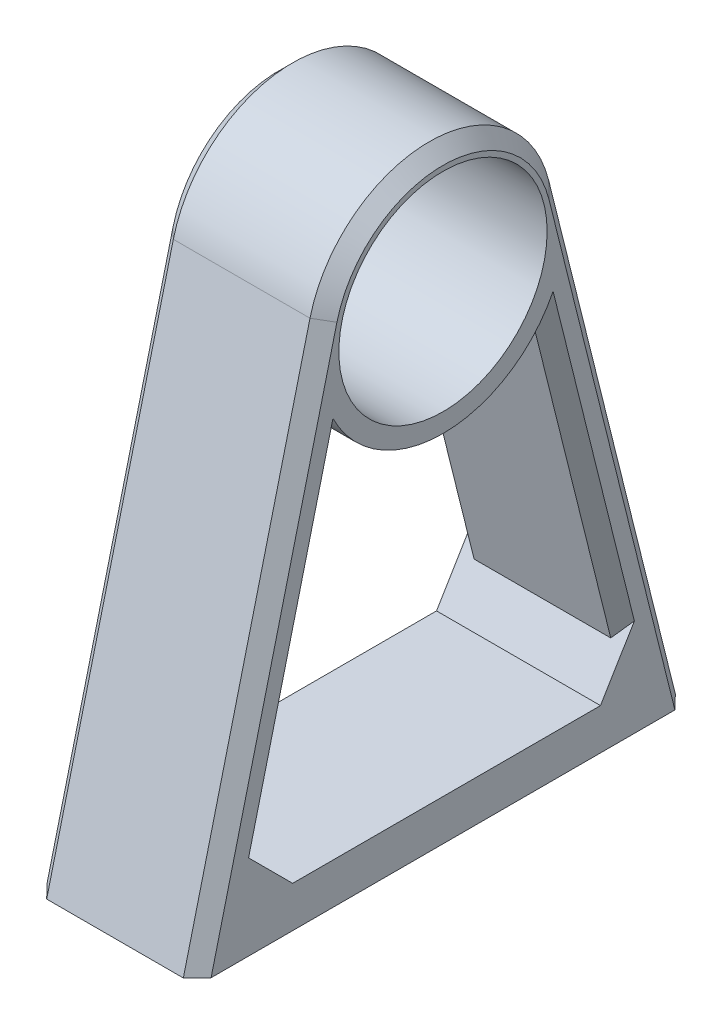
SolidWorks part; units mm, degrees
material "1060-H16"
ref_plane "Płaszczyzna przednia" through (0, 0, 0) normal (0, 0, 1) x (1, 0, 0)
ref_plane "Płaszczyzna górna" through (0, 0, 0) normal (0, 1, 0) x (1, 0, 0)
ref_plane "Płaszczyzna prawa" through (0, 0, 0) normal (1, 0, 0) x (0, 0, -1)
sketch "Szkic1" plane through (0, 0, 0) normal (1, 0, 0) x (0, 0, -1)
  line L0 (0, -45) -> (0, -175)
  line L1 (0, -175) -> (-90, -175)
  line L2 (0, -175) -> (90, -175)
  line L3 (-90, -175) -> (-43.6639, 10.8843)
  line L4 (90, -175) -> (43.6639, 10.8843)
  line L5 (0, -160) -> (70, -160)
  line L6 (0, -160) -> (-70, -160)
  line L7 (-70, -160) -> (-36.6314, -26.137)
  line L8 (70, -160) -> (36.6314, -26.137)
  circle A0 centre (0, 0) radius 38.1
  arc A1 (-36.6314, -26.137) -> (36.6314, -26.137) centre (0, 0) ccw
  arc A2 (43.6639, 10.8843) -> (-43.6639, 10.8843) centre (0, 0) ccw
  dimension "D1" = 76.2
  dimension "D2" = 90
  dimension "D3" = 130
  dimension "D4" = 90
  dimension "D5" = 90
  dimension "D6" = 70
  dimension "D7" = 70
  dimension "D8" = 15
extrude "Dodanie-wyciągnięcie1" add sketch "Szkic1" along normal mid plane 60
chamfer "Sfazowanie1" distance 15 angle 45 2 edges at (0, -160, -70) (0, -160, 70)
chamfer "Sfazowanie2" distance 5 angle 45 10 edges at (30, -82.0579, -66.8319) (30, 45, 0) (30, -82.0579, 66.8319) (-30, -82.0579, -66.8319) (-30, 45, 0) (-30, -82.0579, 66.8319) (-30, -87.065, 51.8192) (-30, -85.7912, -51.5017) (30, -85.7912, -51.5017) (30, -87.065, 51.8192)
